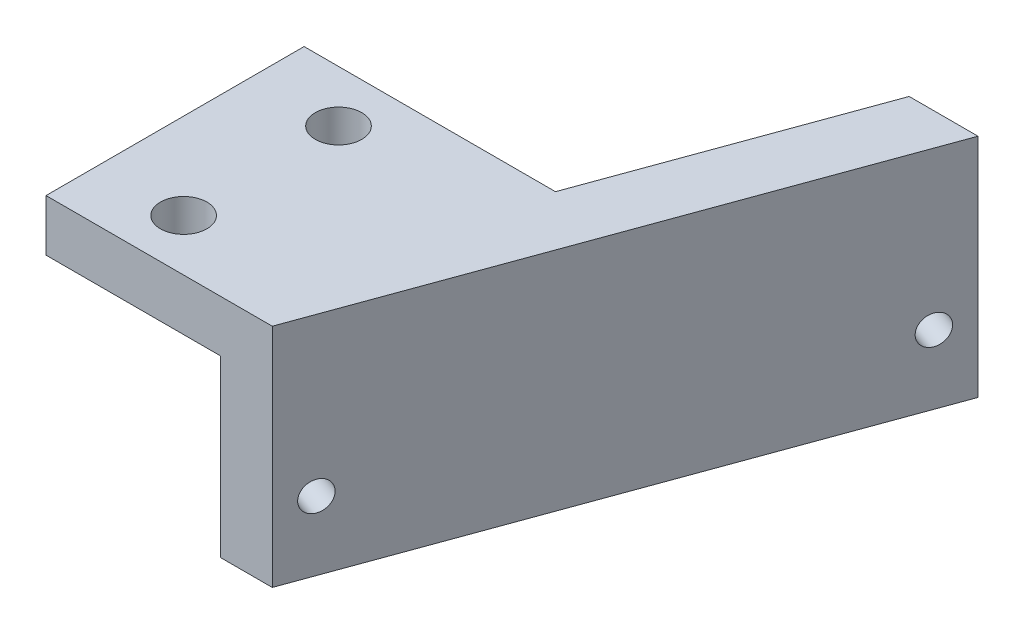
SolidWorks part; units mm, degrees
ref_plane "Front Plane" through (0, 0, 0) normal (0, 0, 1) x (1, 0, 0)
ref_plane "Top Plane" through (0, 0, 0) normal (0, 1, 0) x (1, 0, 0)
ref_plane "Right Plane" through (0, 0, 0) normal (1, 0, 0) x (0, 0, -1)
sketch "Sketch1" plane through (0, 0, 0) normal (0, 0, 1) x (1, 0, 0)
  line L0 (0, 0) -> (0, 20.3)
  line L1 (0, 20.3) -> (-20.3, 20.3)
  line L2 (-20.3, 20.3) -> (-20.3, 26.3)
  line L3 (-20.3, 26.3) -> (6, 26.3)
  line L4 (6, 26.3) -> (6, 0)
  line L5 (6, 0) -> (0, 0)
  dimension "D1" = 6
  dimension "D2" = 6
  dimension "D3" = 20.3
  dimension "D4" = 20.3
extrude "Boss-Extrude1" add sketch "Sketch1" along normal blind 30
sketch "Sketch2" plane through (0, 0, 0) normal (0, -1, 0) x (1, 0, 0)
  line L0 (6, 0) -> (16.9191, 0)
  line L1 (16.9191, 0) -> (6, 30)
  line L2 (6, 30) -> (6, 0)
  dimension "D1" = 70
extrude "Boss-Extrude2" add sketch "Sketch2" against normal up to surface (26.3 mm away) up to face at (-7.15, 26.3, 15)
sketch "Sketch3" plane through (0, 26.3, 0) normal (0, 1, 0) x (1, 0, 0)
  line L0 (16.9191, 0) -> (27.8893, 30.1403)
  line L1 (27.8893, 30.1403) -> (19.8893, 30.1403)
  line L2 (19.8893, 30.1403) -> (8.9191, 0)
  line L3 (16.9191, 0) -> (-20.3, 0) construction
  line L4 (6, -30) -> (16.9191, 0) construction
  line L5 (8.9191, 0) -> (16.9191, 0)
  dimension "D1" = 64
  dimension "D2" = 8
extrude "Boss-Extrude3" add sketch "Sketch3" against normal up to surface (26.3 mm away) up to face at (5.7298, 0, 15)
sketch "Sketch4" plane through (14.9399, 0, 5.4377) normal (0.9397, 0, 0.342) x (0.342, 0, -0.9397)
  line L0 (-26.1387, 8) -> (37.8613, 8) construction
  line L1 (-26.1387, 0) -> (-26.1387, 26.3) construction
  line L2 (37.8613, 0) -> (37.8613, 26.3) construction
  line L3 (5.8613, 8) -> (5.8613, 26.3) construction
  line L4 (-26.1387, 26.3) -> (37.8613, 26.3) construction
  line L5 (37.8613, 0) -> (-26.1387, 0) construction
  circle A0 centre (-22.1387, 8) radius 1.7
  circle A1 centre (33.8613, 8) radius 1.7
  dimension "D1" = 3.4
  dimension "D2" = 28
  dimension "D3" = 8
extrude "Cut-Extrude1" cut sketch "Sketch4" against normal up to surface (8.4597 mm away)
sketch "Sketch5" plane through (14.9399, 0, 5.4377) normal (0.9397, 0, 0.342) x (0.342, 0, -0.9397)
  circle A0 centre (-22.1387, 8) radius 2.95
  circle A1 centre (33.8613, 8) radius 2.95
  dimension "D1" = 5.9
  dimension "D2" = 5.9
extrude "Cut-Extrude2" cut sketch "Sketch5" against normal blind 21 from offset 6 offset against normal yes
sketch "Sketch7" plane through (0, 26.3, 0) normal (0, 1, 0) x (1, 0, 0)
  line L0 (-10.3, 0) -> (-10.3, -30) construction
  line L1 (8.9191, 0) -> (-20.3, 0) construction
  line L2 (6, -30) -> (-20.3, -30) construction
  circle A0 centre (-10.3, -24) radius 2.7
  circle A1 centre (-10.3, -6) radius 2.7
  dimension "D2" = 5.4
  dimension "D3" = 5.4
  dimension "D1" = 10
  dimension "D4" = 6
  dimension "D5" = 6
extrude "Cut-Extrude3" cut sketch "Sketch7" against normal blind 21
